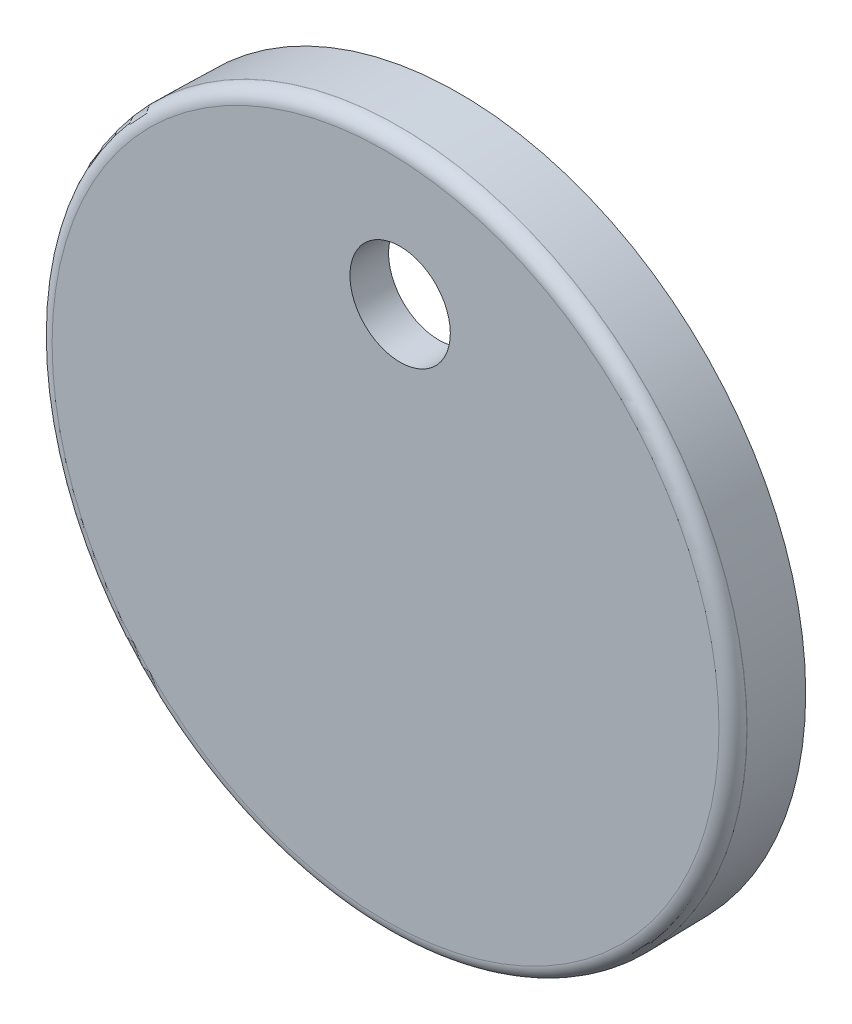
SolidWorks part; units mm, degrees
ref_plane "Front Plane" through (0, 0, 0) normal (0, 0, 1) x (1, 0, 0)
ref_plane "Top Plane" through (0, 0, 0) normal (0, 1, 0) x (1, 0, 0)
ref_plane "Right Plane" through (0, 0, 0) normal (1, 0, 0) x (0, 0, -1)
sketch "Sketch1" plane through (0, 0, 0) normal (0, 0, 1) x (1, 0, 0)
  circle A4 centre (0, 0) radius 49.5
  dimension "D1" = 99
extrude "Boss-Extrude1" add sketch "Sketch1" along normal blind 2 draft 1
sketch "Sketch2" plane through (0, 0, 2) normal (0, 0, 1) x (1, 0, 0)
  circle A0 centre (0.0292, 0.0068) radius 4
  dimension "D1" = 8
extrude "Holder" add sketch "Sketch2" against normal blind 15
sketch "Sketch5" plane through (0, 0, -13) normal (0, 0, -1) x (-1, 0, 0)
  line L4 (-1.5765, 2.192) -> (-1.5765, -2.192)
  arc A0 (-1.5765, -2.192) -> (-1.5765, 2.192) centre (0, 0) ccw
  dimension "D1" = 4.3839
  dimension "D2" = 2.7
extrude "HolderCut" cut sketch "Sketch5" against normal blind 5
fillet "Fillet1" radius 2 1 edges at (49.4651, 0, 2)
sketch "Sketch6" plane through (0, 0, 2) normal (0, 0, 1) x (1, 0, 0)
  circle A0 centre (2.0757, 29.5948) radius 7.15
extrude "CamCut" cut sketch "Sketch6" against normal blind 11 draft 1
sketch "Sketch7" plane through (0, 0, -13) normal (0, 0, -1) x (-1, 0, 0)
  line L2 (-1.6765, 2.2426) -> (-1.6765, -2.2426)
  line L3 (-1.6765, 2.2426) -> (-1.6765, -2.2426)
  arc A2 (-1.6765, -2.2426) -> (-1.6765, 2.2426) centre (0, 0) ccw
  arc A3 (-1.6765, -2.2426) -> (-1.6765, 2.2426) centre (0, 0) ccw
  dimension "D1" = 0.1
extrude "Cut-Extrude1" cut sketch "Sketch7" against normal blind 10
sketch "Sketch8" plane through (0, 0, 0) normal (0, 0, -1) x (-1, 0, 0)
  circle A2 centre (0, 0) radius 49.5
  circle A3 centre (0, 0) radius 49.5
  dimension "D1" = 0
extrude "Boss-Extrude2" add sketch "Sketch8" along normal blind 8.5 draft 1
sketch "Sketch9" plane through (0, 0, -8.5) normal (0, 0, -1) x (-1, 0, 0)
  circle A1 centre (0, 0) radius 4
  circle A2 centre (0, 0) radius 47.8516
  circle A3 centre (0, 0) radius 47.8516
  dimension "D1" = 1.5
extrude "Cut-Extrude5" cut sketch "Sketch9" against normal blind 5 contours A3
sketch "Sketch10" plane through (0, 0, 2) normal (0, 0, 1) x (1, 0, 0)
  circle A2 centre (2.0757, 29.5948) radius 7.15
  circle A3 centre (2.0757, 29.5948) radius 7.15
  dimension "D1" = 0
extrude "Cut-Extrude6" cut sketch "Sketch10" against normal blind 10
